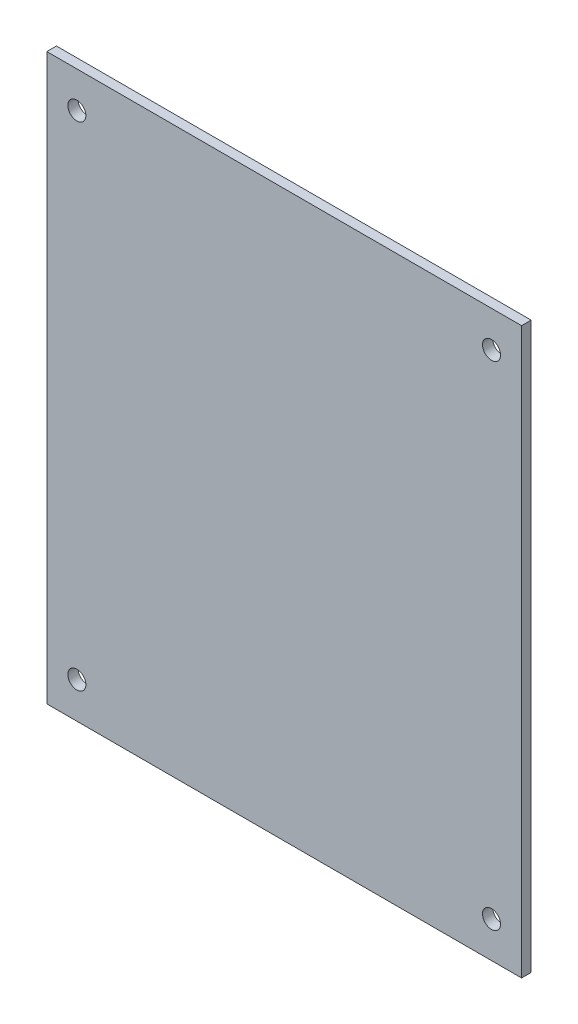
SolidWorks part; units mm, degrees
ref_plane "Front Plane" through (0, 0, 0) normal (0, 0, 1) x (1, 0, 0)
ref_plane "Top Plane" through (0, 0, 0) normal (0, 1, 0) x (1, 0, 0)
ref_plane "Right Plane" through (0, 0, 0) normal (1, 0, 0) x (0, 0, -1)
sketch "Sketch1" plane through (0, 0, 0) normal (0, 0, 1) x (1, 0, 0)
  line L0 (0, -47) -> (0, 47) construction
  line L1 (-39.5, 47) -> (39.5, 47)
  line L2 (-39.5, 47) -> (-39.5, -47)
  line L3 (-39.5, -47) -> (39.5, -47)
  line L4 (39.5, 47) -> (39.5, -47)
  line L5 (-39.5, 0) -> (39.5, 0) construction
  line L6 (0, 0) -> (53, 0) construction
  line L7 (-4.99, 40.3833) -> (5.17, 40.3833) construction
  line L8 (-4.1645, 39.5578) -> (-3.2755, 39.5578) construction
  line L9 (-4.1645, 39.5578) -> (-4.1645, 38.6688) construction
  line L10 (-4.1645, 38.6688) -> (-3.2755, 38.6688) construction
  line L11 (-3.2755, 39.5578) -> (-3.2755, 38.6688) construction
  line L12 (-1.6245, 39.5578) -> (-0.7355, 39.5578) construction
  line L13 (-1.6245, 39.5578) -> (-1.6245, 38.6688) construction
  line L14 (-1.6245, 38.6688) -> (-0.7355, 38.6688) construction
  line L15 (-0.7355, 39.5578) -> (-0.7355, 38.6688) construction
  line L16 (0.9155, 39.5578) -> (1.8045, 39.5578) construction
  line L17 (0.9155, 39.5578) -> (0.9155, 38.6688) construction
  line L18 (0.9155, 38.6688) -> (1.8045, 38.6688) construction
  line L19 (1.8045, 39.5578) -> (1.8045, 38.6688) construction
  line L20 (3.4555, 39.5578) -> (4.3445, 39.5578) construction
  line L21 (3.4555, 39.5578) -> (3.4555, 38.6688) construction
  line L22 (3.4555, 38.6688) -> (4.3445, 38.6688) construction
  line L23 (4.3445, 39.5578) -> (4.3445, 38.6688) construction
  line L24 (-4.1645, 37.0178) -> (-3.2755, 37.0178) construction
  line L25 (-4.1645, 37.0178) -> (-4.1645, 36.1288) construction
  line L26 (-4.1645, 36.1288) -> (-3.2755, 36.1288) construction
  line L27 (-3.2755, 37.0178) -> (-3.2755, 36.1288) construction
  line L28 (-1.6245, 37.0178) -> (-0.7355, 37.0178) construction
  line L29 (-1.6245, 37.0178) -> (-1.6245, 36.1288) construction
  line L30 (-1.6245, 36.1288) -> (-0.7355, 36.1288) construction
  line L31 (-0.7355, 37.0178) -> (-0.7355, 36.1288) construction
  line L32 (0.9155, 37.0178) -> (1.8045, 37.0178) construction
  line L33 (0.9155, 37.0178) -> (0.9155, 36.1288) construction
  line L34 (0.9155, 36.1288) -> (1.8045, 36.1288) construction
  line L35 (1.8045, 37.0178) -> (1.8045, 36.1288) construction
  line L36 (3.4555, 37.0178) -> (4.3445, 37.0178) construction
  line L37 (3.4555, 37.0178) -> (3.4555, 36.1288) construction
  line L38 (3.4555, 36.1288) -> (4.3445, 36.1288) construction
  line L39 (4.3445, 37.0178) -> (4.3445, 36.1288) construction
  line L40 (-4.1645, 21.5578) -> (-3.2755, 21.5578) construction
  line L41 (-4.1645, 21.5578) -> (-4.1645, 20.6688) construction
  line L42 (-4.1645, 20.6688) -> (-3.2755, 20.6688) construction
  line L43 (-3.2755, 21.5578) -> (-3.2755, 20.6688) construction
  line L44 (-1.6245, 21.5578) -> (-0.7355, 21.5578) construction
  line L45 (-1.6245, 21.5578) -> (-1.6245, 20.6688) construction
  line L46 (-1.6245, 20.6688) -> (-0.7355, 20.6688) construction
  line L47 (-0.7355, 21.5578) -> (-0.7355, 20.6688) construction
  line L48 (0.9155, 21.5578) -> (1.8045, 21.5578) construction
  line L49 (0.9155, 21.5578) -> (0.9155, 20.6688) construction
  line L50 (0.9155, 20.6688) -> (1.8045, 20.6688) construction
  line L51 (1.8045, 21.5578) -> (1.8045, 20.6688) construction
  line L52 (3.4555, 21.5578) -> (4.3445, 21.5578) construction
  line L53 (3.4555, 21.5578) -> (3.4555, 20.6688) construction
  line L54 (3.4555, 20.6688) -> (4.3445, 20.6688) construction
  line L55 (4.3445, 21.5578) -> (4.3445, 20.6688) construction
  line L56 (-4.1645, 19.0178) -> (-3.2755, 19.0178) construction
  line L57 (-4.1645, 19.0178) -> (-4.1645, 18.1288) construction
  line L58 (-4.1645, 18.1288) -> (-3.2755, 18.1288) construction
  line L59 (-3.2755, 19.0178) -> (-3.2755, 18.1288) construction
  line L60 (-1.6245, 19.0178) -> (-0.7355, 19.0178) construction
  line L61 (-1.6245, 19.0178) -> (-1.6245, 18.1288) construction
  line L62 (-1.6245, 18.1288) -> (-0.7355, 18.1288) construction
  line L63 (-0.7355, 19.0178) -> (-0.7355, 18.1288) construction
  line L64 (0.9155, 19.0178) -> (1.8045, 19.0178) construction
  line L65 (0.9155, 19.0178) -> (0.9155, 18.1288) construction
  line L66 (0.9155, 18.1288) -> (1.8045, 18.1288) construction
  line L67 (1.8045, 19.0178) -> (1.8045, 18.1288) construction
  line L68 (3.4555, 19.0178) -> (4.3445, 19.0178) construction
  line L69 (3.4555, 19.0178) -> (3.4555, 18.1288) construction
  line L70 (3.4555, 18.1288) -> (4.3445, 18.1288) construction
  line L71 (4.3445, 19.0178) -> (4.3445, 18.1288) construction
  line L72 (-4.99, 40.3833) -> (-4.99, 35.3033) construction
  line L73 (-4.99, 35.3033) -> (5.17, 35.3033) construction
  line L74 (5.17, 40.3833) -> (5.17, 35.3033) construction
  line L75 (-4.99, 22.3833) -> (5.17, 22.3833) construction
  line L76 (-4.99, 22.3833) -> (-4.99, 17.3033) construction
  line L77 (-4.99, 17.3033) -> (5.17, 17.3033) construction
  line L78 (5.17, 22.3833) -> (5.17, 17.3033) construction
  line L80 (0, 0) -> (-53, 0) construction
  line L82 (0, 0) -> (0, 53) construction
  line L83 (0, 0) -> (0, -53) construction
  line L84 (-39.5, 29.5) -> (-20, 29.5) construction
  line L85 (-53, 53) -> (53, 53) construction
  line L86 (-53, 53) -> (-53, -53) construction
  line L87 (-53, -53) -> (53, -53) construction
  line L88 (53, 53) -> (53, -53) construction
  line L89 (3.75, -42.0047) -> (-3.75, -42.0047) construction
  line L90 (3.75, -42.0047) -> (3.75, -47) construction
  line L92 (-3.75, -42.0047) -> (-3.75, -47) construction
  line L93 (-20, 29.5) -> (-20, 11.5) construction
  line L94 (-20, 11.5) -> (-39.5, 11.5) construction
  line L95 (-39.7244, -12.8) -> (-22.1358, -12.8) construction
  line L96 (-22.1358, -12.8) -> (-22.1358, -28.8) construction
  line L97 (-22.1358, -28.8) -> (-39.5, -28.8) construction
  circle A0 centre (-34.5, 41) radius 1.5
  circle A1 centre (0, 0) radius 5 construction
  circle A2 centre (-16.0867, 16.0867) radius 1.25 construction
  circle A3 centre (-32.5, 24.9) radius 1.25 construction
  circle A4 centre (16.0867, 16.0867) radius 1.25 construction
  circle A5 centre (32.5, 24.9) radius 1.25 construction
  circle A6 centre (16.0867, -16.0867) radius 1.25 construction
  circle A7 centre (32.5, -24.9) radius 1.25 construction
  circle A8 centre (-16.0867, -16.0867) radius 1.25 construction
  circle A9 centre (-32.5, -24.9) radius 1.25 construction
  circle A10 centre (34.5, 41) radius 1.5
  circle A11 centre (34.5, -41) radius 1.5
  circle A12 centre (-34.5, -41) radius 1.5
  circle A13 centre (-34.5, 41) radius 4.5 construction
  circle A14 centre (34.5, 41) radius 4.5 construction
  circle A15 centre (-34.5, -41) radius 4.5 construction
  circle A16 centre (34.5, -41) radius 4.5 construction
  point P68 (53, 0)
  point P69 (-53, 0)
  point P74 (0, 53)
  point P80 (0, -53)
  dimension "D1" = 3
  dimension "D4" = 9
  dimension "D2" = 5
  dimension "D3" = 6
  dimension "D5" = 106
  dimension "D6" = 106
  dimension "D7" = 6
  dimension "D8" = 3.75
  dimension "D9" = 3.75
  dimension "D10" = 4.9953
  dimension "D11" = 17.5
  dimension "D12" = 18
  dimension "D13" = 19.5
  dimension "D14" = 34.2
  dimension "D15" = 16
  dimension "D16" = 17.3642
extrude "Boss-Extrude1" add sketch "Sketch1" along normal blind 1.6
sketch "Sketch2" plane through (0, 0, 0) normal (0, 0, 1) x (1, 0, 0)
  line L0 (0, -47) -> (0, 47) construction
  line L1 (-39.5, 47) -> (39.5, 47) construction
  line L2 (-39.5, 47) -> (-39.5, -47) construction
  line L3 (-39.5, -47) -> (39.5, -47) construction
  line L4 (39.5, 47) -> (39.5, -47) construction
  line L5 (-39.5, 0) -> (39.5, 0) construction
  line L6 (0, 0) -> (53, 0) construction
  line L7 (-4.99, 40.3833) -> (5.17, 40.3833) construction
  line L8 (-4.1645, 39.5578) -> (-3.2755, 39.5578)
  line L9 (-4.1645, 39.5578) -> (-4.1645, 38.6688)
  line L10 (-4.1645, 38.6688) -> (-3.2755, 38.6688)
  line L11 (-3.2755, 39.5578) -> (-3.2755, 38.6688)
  line L12 (-1.6245, 39.5578) -> (-0.7355, 39.5578)
  line L13 (-1.6245, 39.5578) -> (-1.6245, 38.6688)
  line L14 (-1.6245, 38.6688) -> (-0.7355, 38.6688)
  line L15 (-0.7355, 39.5578) -> (-0.7355, 38.6688)
  line L16 (0.9155, 39.5578) -> (1.8045, 39.5578)
  line L17 (0.9155, 39.5578) -> (0.9155, 38.6688)
  line L18 (0.9155, 38.6688) -> (1.8045, 38.6688)
  line L19 (1.8045, 39.5578) -> (1.8045, 38.6688)
  line L20 (3.4555, 39.5578) -> (4.3445, 39.5578)
  line L21 (3.4555, 39.5578) -> (3.4555, 38.6688)
  line L22 (3.4555, 38.6688) -> (4.3445, 38.6688)
  line L23 (4.3445, 39.5578) -> (4.3445, 38.6688)
  line L24 (-4.1645, 37.0178) -> (-3.2755, 37.0178)
  line L25 (-4.1645, 37.0178) -> (-4.1645, 36.1288)
  line L26 (-4.1645, 36.1288) -> (-3.2755, 36.1288)
  line L27 (-3.2755, 37.0178) -> (-3.2755, 36.1288)
  line L28 (-1.6245, 37.0178) -> (-0.7355, 37.0178)
  line L29 (-1.6245, 37.0178) -> (-1.6245, 36.1288)
  line L30 (-1.6245, 36.1288) -> (-0.7355, 36.1288)
  line L31 (-0.7355, 37.0178) -> (-0.7355, 36.1288)
  line L32 (0.9155, 37.0178) -> (1.8045, 37.0178)
  line L33 (0.9155, 37.0178) -> (0.9155, 36.1288)
  line L34 (0.9155, 36.1288) -> (1.8045, 36.1288)
  line L35 (1.8045, 37.0178) -> (1.8045, 36.1288)
  line L36 (3.4555, 37.0178) -> (4.3445, 37.0178)
  line L37 (3.4555, 37.0178) -> (3.4555, 36.1288)
  line L38 (3.4555, 36.1288) -> (4.3445, 36.1288)
  line L39 (4.3445, 37.0178) -> (4.3445, 36.1288)
  line L40 (-4.1645, 21.5578) -> (-3.2755, 21.5578)
  line L41 (-4.1645, 21.5578) -> (-4.1645, 20.6688)
  line L42 (-4.1645, 20.6688) -> (-3.2755, 20.6688)
  line L43 (-3.2755, 21.5578) -> (-3.2755, 20.6688)
  line L44 (-1.6245, 21.5578) -> (-0.7355, 21.5578)
  line L45 (-1.6245, 21.5578) -> (-1.6245, 20.6688)
  line L46 (-1.6245, 20.6688) -> (-0.7355, 20.6688)
  line L47 (-0.7355, 21.5578) -> (-0.7355, 20.6688)
  line L48 (0.9155, 21.5578) -> (1.8045, 21.5578)
  line L49 (0.9155, 21.5578) -> (0.9155, 20.6688)
  line L50 (0.9155, 20.6688) -> (1.8045, 20.6688)
  line L51 (1.8045, 21.5578) -> (1.8045, 20.6688)
  line L52 (3.4555, 21.5578) -> (4.3445, 21.5578)
  line L53 (3.4555, 21.5578) -> (3.4555, 20.6688)
  line L54 (3.4555, 20.6688) -> (4.3445, 20.6688)
  line L55 (4.3445, 21.5578) -> (4.3445, 20.6688)
  line L56 (-4.1645, 19.0178) -> (-3.2755, 19.0178)
  line L57 (-4.1645, 19.0178) -> (-4.1645, 18.1288)
  line L58 (-4.1645, 18.1288) -> (-3.2755, 18.1288)
  line L59 (-3.2755, 19.0178) -> (-3.2755, 18.1288)
  line L60 (-1.6245, 19.0178) -> (-0.7355, 19.0178)
  line L61 (-1.6245, 19.0178) -> (-1.6245, 18.1288)
  line L62 (-1.6245, 18.1288) -> (-0.7355, 18.1288)
  line L63 (-0.7355, 19.0178) -> (-0.7355, 18.1288)
  line L64 (0.9155, 19.0178) -> (1.8045, 19.0178)
  line L65 (0.9155, 19.0178) -> (0.9155, 18.1288)
  line L66 (0.9155, 18.1288) -> (1.8045, 18.1288)
  line L67 (1.8045, 19.0178) -> (1.8045, 18.1288)
  line L68 (3.4555, 19.0178) -> (4.3445, 19.0178)
  line L69 (3.4555, 19.0178) -> (3.4555, 18.1288)
  line L70 (3.4555, 18.1288) -> (4.3445, 18.1288)
  line L71 (4.3445, 19.0178) -> (4.3445, 18.1288)
  line L72 (-4.99, 40.3833) -> (-4.99, 35.3033) construction
  line L73 (-4.99, 35.3033) -> (5.17, 35.3033) construction
  line L74 (5.17, 40.3833) -> (5.17, 35.3033) construction
  line L75 (-4.99, 22.3833) -> (5.17, 22.3833) construction
  line L76 (-4.99, 22.3833) -> (-4.99, 17.3033) construction
  line L77 (-4.99, 17.3033) -> (5.17, 17.3033) construction
  line L78 (5.17, 22.3833) -> (5.17, 17.3033) construction
  line L80 (0, 0) -> (-53, 0) construction
  line L82 (0, 0) -> (0, 53) construction
  line L83 (0, 0) -> (0, -53) construction
  line L84 (-39.5, 29.5) -> (-20, 29.5)
  line L85 (-53, 53) -> (53, 53) construction
  line L86 (-53, 53) -> (-53, -53) construction
  line L87 (-53, -53) -> (53, -53) construction
  line L88 (53, 53) -> (53, -53) construction
  line L89 (3.75, -42.0047) -> (-3.75, -42.0047)
  line L90 (3.75, -42.0047) -> (3.75, -47)
  line L92 (-3.75, -42.0047) -> (-3.75, -47)
  line L93 (-20, 29.5) -> (-20, 11.5)
  line L94 (-20, 11.5) -> (-39.5, 11.5)
  line L95 (-39.7244, -12.8) -> (-22.1358, -12.8)
  line L96 (-22.1358, -12.8) -> (-22.1358, -28.8)
  line L97 (-22.1358, -28.8) -> (-39.5, -28.8)
  line L98 (-39.5, 29.5) -> (-39.5, 11.5)
  line L99 (-39.7244, -12.8) -> (-39.5, -28.8)
  line L100 (-3.75, -47) -> (3.75, -47)
  circle A0 centre (-34.5, 41) radius 1.5
  circle A1 centre (0, 0) radius 5
  circle A2 centre (-16.0867, 16.0867) radius 1.25
  circle A3 centre (-32.5, 24.9) radius 1.25
  circle A4 centre (16.0867, 16.0867) radius 1.25
  circle A5 centre (32.5, 24.9) radius 1.25
  circle A6 centre (16.0867, -16.0867) radius 1.25
  circle A7 centre (32.5, -24.9) radius 1.25
  circle A8 centre (-16.0867, -16.0867) radius 1.25
  circle A9 centre (-32.5, -24.9) radius 1.25
  circle A10 centre (34.5, 41) radius 1.5
  circle A11 centre (34.5, -41) radius 1.5
  circle A12 centre (-34.5, -41) radius 1.5
  circle A13 centre (-34.5, 41) radius 4.5
  circle A14 centre (34.5, 41) radius 4.5
  circle A15 centre (-34.5, -41) radius 4.5
  circle A16 centre (34.5, -41) radius 4.5
  point P68 (53, 0)
  point P69 (-53, 0)
  point P74 (0, 53)
  point P80 (0, -53)
  dimension "D1" = 3
  dimension "D4" = 9
  dimension "D2" = 5
  dimension "D3" = 6
  dimension "D5" = 106
  dimension "D6" = 106
  dimension "D7" = 6
  dimension "D8" = 3.75
  dimension "D9" = 3.75
  dimension "D10" = 4.9953
  dimension "D11" = 17.5
  dimension "D12" = 18
  dimension "D13" = 19.5
  dimension "D14" = 34.2
  dimension "D15" = 16
  dimension "D16" = 17.3642
extrude "Boss-Extrude2" add sketch "Sketch2" against normal blind 0.1
